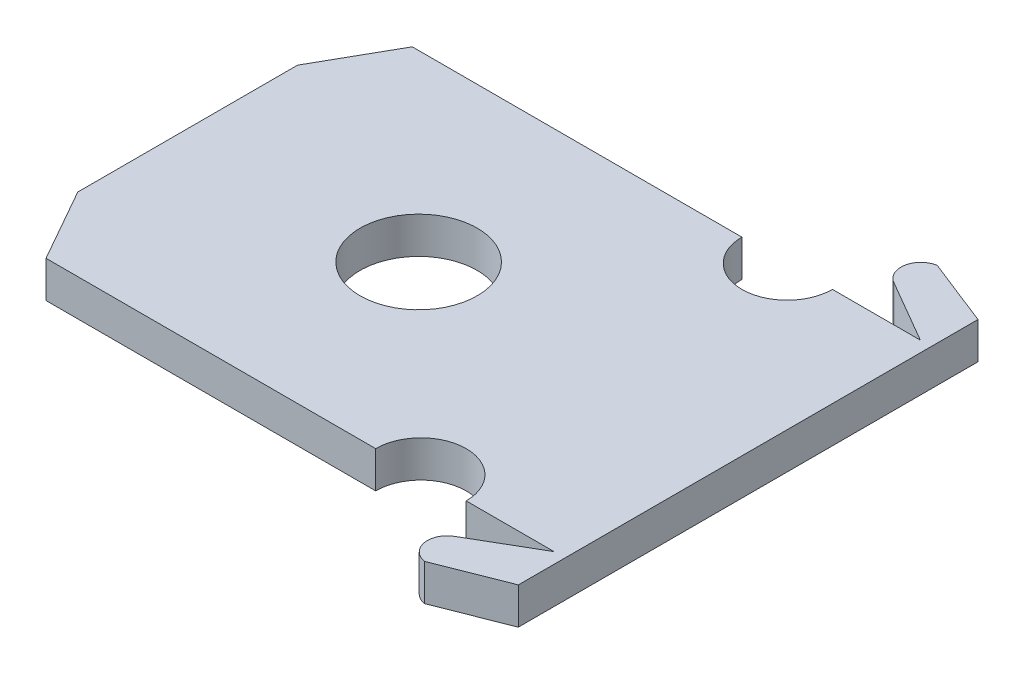
SolidWorks part; units mm, degrees
ref_plane "Front Plane" through (0, 0, 0) normal (0, 0, 1) x (1, 0, 0)
ref_plane "Top Plane" through (0, 0, 0) normal (0, 1, 0) x (1, 0, 0)
ref_plane "Right Plane" through (0, 0, 0) normal (1, 0, 0) x (0, 0, -1)
sketch "Sketch1" plane through (0, 0, 0) normal (0, 1, 0) x (1, 0, 0)
  line L0 (0, 0) -> (-9.5285, 0) construction
  line L1 (0, 1.5) -> (0, -1.5)
  line L2 (0, -1.5) -> (0.5664, -2.5)
  line L3 (0.5664, -2.5) -> (5.0664, -2.5)
  line L4 (6.3024, -2.5) -> (7.5024, -2.5)
  line L5 (7.5024, -2.5) -> (6.6402, -3.0001)
  line L6 (6.7331, -3.499) -> (7.6514, -3.1375)
  line L7 (7.6514, -3.1375) -> (7.6514, 3.1375)
  line L8 (6.7331, 3.499) -> (7.6514, 3.1375)
  line L9 (7.5024, 2.5) -> (6.6402, 3.0001)
  line L10 (6.3024, 2.5) -> (7.5024, 2.5)
  line L11 (0.5664, 2.5) -> (5.0664, 2.5)
  line L12 (0, 1.5) -> (0.5664, 2.5)
  arc A0 (5.0664, -2.5) -> (6.3024, -2.5) centre (5.6844, -2.5) cw
  arc A1 (6.6402, -3.0001) -> (6.7331, -3.499) centre (6.7753, -3.2331) ccw
  arc A2 (6.6402, 3.0001) -> (6.7331, 3.499) centre (6.7753, 3.2331) cw
  arc A3 (5.0664, 2.5) -> (6.3024, 2.5) centre (5.6844, 2.5) ccw
  circle A4 centre (3.1534, 0) radius 0.8
  point P16 (0, 0)
  point P17 (7.6514, 0)
  dimension "D1" = 1.5
  dimension "D2" = 1
  dimension "D3" = 1.2
  dimension "6" = 4.5
extrude "Boss-Extrude1" add sketch "Sketch1" along normal blind 0.5 contours A4 L0 | L0 A4 | L3 A0 L4 L5 A1 L6 L7 L8 A2 L9 L10 A3 L11 L12 L1 L2
